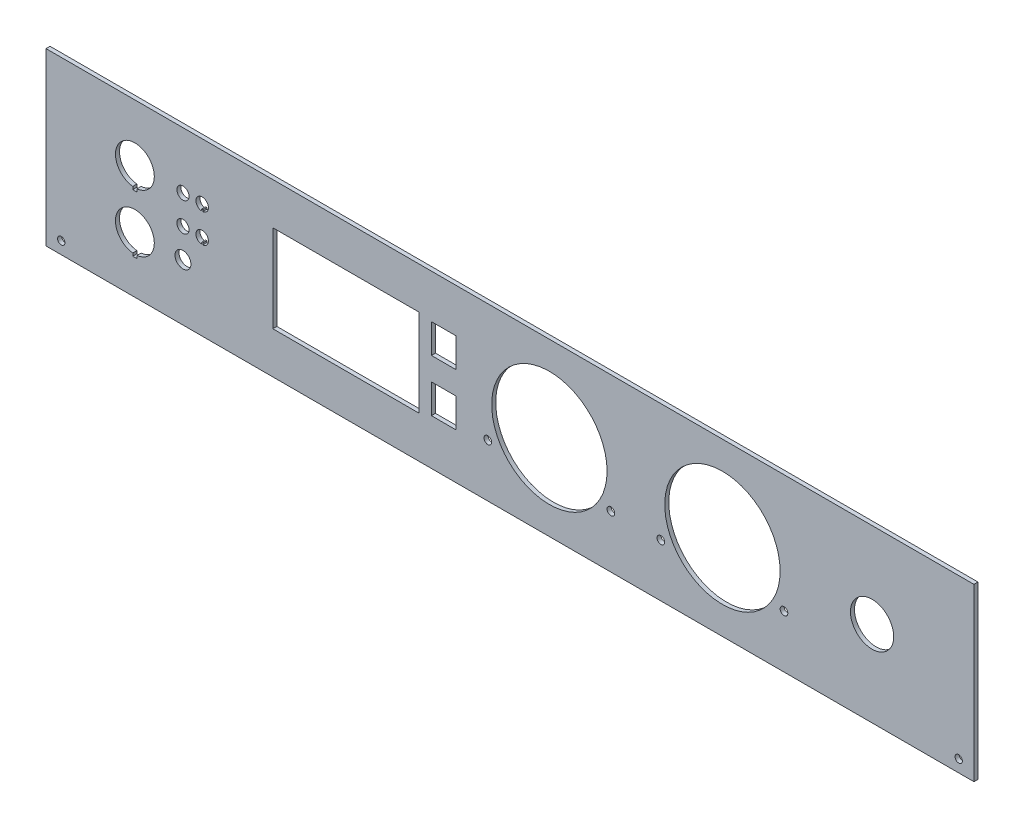
SolidWorks part; units mm, degrees
ref_plane "Front Plane" through (0, 0, 0) normal (0, 0, 1) x (1, 0, 0)
ref_plane "Top Plane" through (0, 0, 0) normal (0, 1, 0) x (1, 0, 0)
ref_plane "Right Plane" through (0, 0, 0) normal (1, 0, 0) x (0, 0, -1)
sketch "Rack rails" plane through (0, 0, 0) normal (0, 0, 1) x (1, 0, 0)
  line L0 (0, 155.9276) -> (0, -163.9347) construction
  line L1 (-225.425, 155.575) -> (-241.3, 155.575)
  line L2 (-225.425, 155.575) -> (-225.425, -22.225)
  line L3 (-225.425, -22.225) -> (-241.3, -22.225)
  line L4 (-241.3, 155.575) -> (-241.3, -22.225)
  line L5 (225.425, -22.225) -> (241.3, -22.225)
  line L6 (225.425, 155.575) -> (225.425, -22.225)
  line L7 (225.425, 155.575) -> (241.3, 155.575)
  line L8 (241.3, 155.575) -> (241.3, -22.225)
  line L9 (-233.3625, 15.875) -> (-233.3625, 60.325) construction
  line L10 (-241.3, 22.225) -> (241.3, 22.225) construction
  line L11 (241.3, 66.675) -> (-241.3, 66.675) construction
  line L12 (-241.3, 111.125) -> (241.3, 111.125) construction
  circle A0 centre (-233.3625, 15.875) radius 1.8987
  circle A1 centre (233.3625, 15.875) radius 1.8987
  circle A2 centre (-233.3625, 0) radius 1.8987
  circle A3 centre (233.3625, 0) radius 1.8987
  circle A4 centre (-233.3625, -15.875) radius 1.8987
  circle A5 centre (233.3625, -15.875) radius 1.8987
  circle A6 centre (-233.3625, 60.325) radius 1.8987
  circle A7 centre (-233.3625, 44.45) radius 1.8987
  circle A8 centre (-233.3625, 28.575) radius 1.8987
  circle A9 centre (-233.3625, 104.775) radius 1.8987
  circle A10 centre (-233.3625, 88.9) radius 1.8987
  circle A11 centre (-233.3625, 73.025) radius 1.8987
  circle A12 centre (-233.3625, 149.225) radius 1.8987
  circle A13 centre (-233.3625, 133.35) radius 1.8987
  circle A14 centre (-233.3625, 117.475) radius 1.8987
  circle A15 centre (233.3625, 117.475) radius 1.8987
  circle A16 centre (233.3625, 133.35) radius 1.8987
  circle A17 centre (233.3625, 149.225) radius 1.8987
  circle A18 centre (233.3625, 73.025) radius 1.8987
  circle A19 centre (233.3625, 88.9) radius 1.8987
  circle A20 centre (233.3625, 104.775) radius 1.8987
  circle A21 centre (233.3625, 28.575) radius 1.8987
  circle A22 centre (233.3625, 44.45) radius 1.8987
  circle A23 centre (233.3625, 60.325) radius 1.8987
  point P21 (-233.3625, 155.575)
  point P24 (233.3625, 155.575)
  dimension "D7" = 3.7973
  dimension "D1" = 482.6
  dimension "D2" = 450.85
  dimension "D3" = 15.875
  dimension "D4" = 15.875
  dimension "D6" = 44.45
  dimension "D8" = 6.35
  dimension "D9" = 6.35
  dimension "D10" = 6.35
  dimension "D11" = 6.35
  dimension "D12" = 6.35
  dimension "D5" = 4
sketch "Sketch1" plane through (0, 0, 0) normal (0, 0, 1) x (1, 0, 0)
  line L0 (-225.425, -22.225) -> (-241.3, -22.225) construction
  line L1 (-241.3, 66.675) -> (241.3, 66.675)
  line L2 (-241.3, 66.675) -> (-241.3, -22.225)
  line L3 (-241.3, -22.225) -> (241.3, -22.225)
  line L4 (241.3, 66.675) -> (241.3, -22.225)
  line L5 (-241.3, 66.675) -> (241.3, -22.225) construction
  line L6 (-241.3, -22.225) -> (241.3, 66.675) construction
  point P0 (0, 22.225)
  dimension "D1" = 482.6
  dimension "D2" = 88.9
extrude "Front panel" add sketch "Sketch1" along normal blind 2.1
sketch "Sketch7" plane through (0, 0, 2.1) normal (0, 0, 1) x (1, 0, 0)
  circle A0 centre (-233.3625, -15.875) radius 1.8987 construction
  circle A1 centre (233.3625, -15.875) radius 1.8987 construction
  circle A2 centre (-233.3625, -15.875) radius 1.8987
  circle A3 centre (233.3625, -15.875) radius 1.8987
extrude "Mounting holes" cut sketch "Sketch7" against normal up to next
sketch "Sketch2" plane through (0, 0, 2.1) normal (0, 0, 1) x (1, 0, 0)
  line L0 (-195.0759, 37.225) -> (-195.0759, 7.225) construction
  line L1 (-196.1759, 27.1851) -> (-196.1759, 25.725)
  line L2 (-196.1759, 25.725) -> (-193.9759, 25.725)
  line L3 (-193.9759, 25.725) -> (-193.9759, 27.1851)
  line L4 (-196.1759, -2.8149) -> (-196.1759, -4.275)
  line L5 (-196.1759, -4.275) -> (-193.9759, -4.275)
  line L6 (-193.9759, -4.275) -> (-193.9759, -2.8149)
  line L7 (-241.3, 22.225) -> (241.3, 22.225) construction
  arc A0 (-193.9759, 27.1851) -> (-196.1759, 27.1851) centre (-195.0759, 37.225) ccw
  arc A1 (-193.9759, -2.8149) -> (-196.1759, -2.8149) centre (-195.0759, 7.225) ccw
  point P4 (-195.0759, 22.225)
  point P12 (-195.0759, 25.725)
  dimension "D1" = 20.2
  dimension "D2" = 30
  dimension "D4" = 2.2
  dimension "D5" = 11.5
  dimension "D6" = 11.5
extrude "Start/stop" cut sketch "Sketch2" against normal through all
sketch "Sketch3" plane through (0, 0, 2.1) normal (0, 0, 1) x (1, 0, 0)
  line L0 (-195.0759, 37.225) -> (-195.0759, 7.225) construction
  line L1 (-160.3759, 33.9889) -> (-160.3759, 34.875)
  line L2 (-160.3759, 34.875) -> (-159.7759, 34.875)
  line L3 (-159.7759, 34.875) -> (-159.7759, 33.9889)
  line L4 (-160.3759, 18.9889) -> (-160.3759, 19.875)
  line L5 (-160.3759, 19.875) -> (-159.7759, 19.875)
  line L6 (-159.7759, 19.875) -> (-159.7759, 18.9889)
  arc A0 (-159.7759, 33.9889) -> (-160.3759, 33.9889) centre (-160.0759, 37.225) ccw
  circle A1 centre (-170.0759, 37.225) radius 3.175
  circle A2 centre (-170.0759, 22.225) radius 3.175
  circle A3 centre (-195.0759, 37.225) radius 10.1 construction
  circle A4 centre (-195.0759, 7.225) radius 10.1 construction
  circle A5 centre (-195.0759, 37.225) radius 10.1 construction
  circle A6 centre (-195.0759, 7.225) radius 10.1 construction
  arc A7 (-159.7759, 18.9889) -> (-160.3759, 18.9889) centre (-160.0759, 22.225) ccw
  point P9 (-160.0759, 22.225)
  point P14 (-195.0759, 22.225)
  point P17 (-160.0759, 34.875)
  point P22 (-160.0759, 19.875)
  dimension "D1" = 6.35
  dimension "D2" = 6.5
  dimension "D3" = 5.6
  dimension "D4" = 15
  dimension "D5" = 0.6
  dimension "D6" = 10
  dimension "D7" = 35
extrude "Mode select" cut sketch "Sketch3" against normal through all
sketch "Sketch4" plane through (0, 0, 2.1) normal (0, 0, 1) x (1, 0, 0)
  line L0 (-195.0759, 37.225) -> (-195.0759, 7.225) construction
  line L1 (-123.3408, 44.975) -> (-47.3408, 44.975)
  line L2 (-123.3408, 44.975) -> (-123.3408, -0.525)
  line L3 (-123.3408, -0.525) -> (-47.3408, -0.525)
  line L4 (-47.3408, 44.975) -> (-47.3408, -0.525)
  line L5 (-123.3408, 44.975) -> (-47.3408, -0.525) construction
  line L6 (-123.3408, -0.525) -> (-47.3408, 44.975) construction
  circle A4 centre (-195.0759, 7.225) radius 10.1 construction
  circle A5 centre (-195.0759, 7.225) radius 10.1 construction
  point P0 (-85.3408, 22.225)
  point P10 (-195.0759, 22.225)
  dimension "D1" = 45.5
  dimension "D2" = 76
extrude "LCD cutout" cut sketch "Sketch4" against normal through all
sketch "Sketch5" plane through (0, 0, 2.1) normal (0, 0, 1) x (1, 0, 0)
  line L1 (-241.3, 22.225) -> (241.3, 22.225) construction
  circle A0 centre (188.309, 22.225) radius 11.25
  point P4 (-166.8287, 22.225)
  dimension "D1" = 22.5
extrude "E-stop cutout" cut sketch "Sketch5" against normal through all
sketch "Sketch6" plane through (0, 0, 2.1) normal (0, 0, 1) x (1, 0, 0)
  line L0 (-42.3408, -0.525) -> (159.8496, -0.525) construction
  line L1 (-40.8808, 43.9275) -> (-28.1808, 43.9275)
  line L2 (-40.8808, 43.9275) -> (-40.8808, 28.6875)
  line L3 (-40.8808, 28.6875) -> (-28.1808, 28.6875)
  line L4 (-28.1808, 43.9275) -> (-28.1808, 28.6875)
  line L5 (-40.8808, 43.9275) -> (-28.1808, 28.6875) construction
  line L6 (-40.8808, 28.6875) -> (-28.1808, 43.9275) construction
  line L7 (-40.8808, 16.81) -> (-28.1808, 16.81)
  line L8 (-40.8808, 16.81) -> (-40.8808, 1.57)
  line L9 (-40.8808, 1.57) -> (-28.1808, 1.57)
  line L10 (-28.1808, 16.81) -> (-28.1808, 1.57)
  line L11 (-40.8808, 16.81) -> (-28.1808, 1.57) construction
  line L12 (-40.8808, 1.57) -> (-28.1808, 16.81) construction
  line L13 (-123.3408, -0.525) -> (-47.3408, -0.525) construction
  line L14 (-42.3408, 44.975) -> (158.6931, 44.975) construction
  line L15 (-47.3408, 44.975) -> (-123.3408, 44.975) construction
  line L16 (-42.3408, 44.975) -> (-42.3408, 20.3374) construction
  line L17 (-42.3408, -0.525) -> (-42.3408, 12.4166) construction
  line L18 (-47.3408, -0.525) -> (-47.3408, 44.975) construction
  point P0 (-34.5308, 36.3075)
  point P5 (-34.5308, 9.19)
  dimension "D1" = 15.24
  dimension "D2" = 12.7
  dimension "D3" = 2.095
  dimension "D4" = 2.095
  dimension "D5" = 1.46
  dimension "D6" = 1.46
  dimension "D7" = 5
extrude "LCD pushbuttons" cut sketch "Sketch6" against normal through all
sketch "Sketch8" plane through (0, 0, 2.1) normal (0, 0, 1) x (1, 0, 0)
  circle A0 centre (-170.0759, 7.225) radius 4.15
  point P2 (-170.0759, 22.225)
  dimension "D1" = 8.3
  dimension "D2" = 15
extrude "ERROR indicator" cut sketch "Sketch8" against normal up to next
sketch "Panel meter cutout" plane through (0, 0, 2.1) normal (0, 0, 1) x (1, 0, 0)
  line L0 (-11.5114, 5.225) -> (52.4886, 5.225) construction
  line L2 (-19.5114, 54.225) -> (60.4886, 54.225) construction
  line L3 (-19.5114, 54.225) -> (-19.5114, -9.775) construction
  line L4 (-19.5114, -9.775) -> (60.4886, -9.775) construction
  line L5 (60.4886, 54.225) -> (60.4886, -9.775) construction
  line L6 (-19.5114, 54.225) -> (60.4886, -9.775) construction
  line L7 (-19.5114, -9.775) -> (60.4886, 54.225) construction
  circle A0 centre (20.4886, 22.225) radius 30
  circle A1 centre (52.4886, 5.225) radius 2
  circle A2 centre (-11.5114, 5.225) radius 2
  point P6 (20.4886, 5.225)
  dimension "D1" = 60
  dimension "D4" = 4
  dimension "D2" = 17
  dimension "D3" = 64
  dimension "D5" = 64
  dimension "D6" = 80
extrude "Panel meter" cut sketch "Panel meter cutout" against normal through all
pattern_linear "LPattern1" count 2 spacing 90 along (1, 0, 0) of "Panel meter"
equation "\"D3@Panel meter cutout\"=32mm*2"
